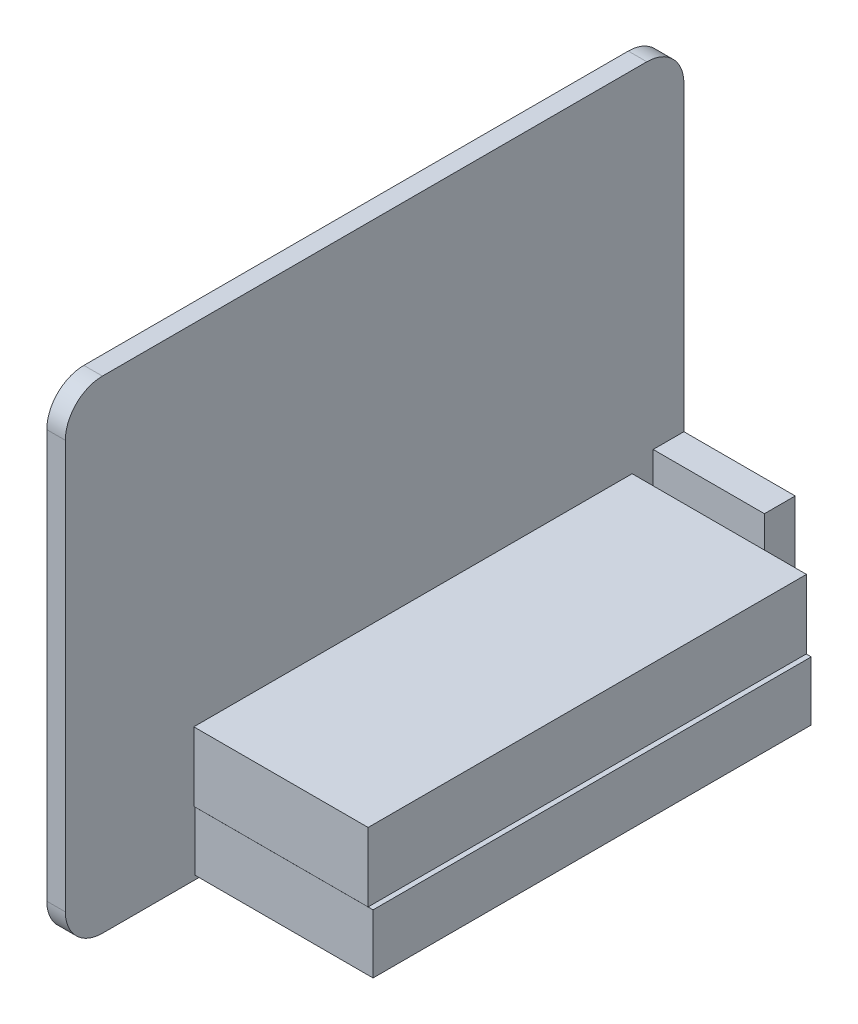
SolidWorks part; units mm, degrees
ref_plane "Front Plane" through (0, 0, 0) normal (0, 0, 1) x (1, 0, 0)
ref_plane "Top Plane" through (0, 0, 0) normal (0, 1, 0) x (1, 0, 0)
ref_plane "Right Plane" through (0, 0, 0) normal (1, 0, 0) x (0, 0, -1)
sketch "Sketch1" plane through (0, 0, 0) normal (1, 0, 0) x (0, 0, -1)
  line L1 (-15.4815, 15.6159) -> (131.2922, 15.6159)
  line L2 (-25.4815, 5.6159) -> (-25.4815, -104.4885)
  line L3 (-15.4815, -114.4885) -> (131.2922, -114.4885)
  line L4 (141.2922, 5.6159) -> (141.2922, -104.4885)
  arc A0 (131.2922, -114.4885) -> (141.2922, -104.4885) centre (131.2922, -104.4885) ccw
  arc A1 (-15.4815, -114.4885) -> (-25.4815, -104.4885) centre (-15.4815, -104.4885) cw
  arc A2 (-15.4815, 15.6159) -> (-25.4815, 5.6159) centre (-15.4815, 5.6159) ccw
  arc A3 (131.2922, 15.6159) -> (141.2922, 5.6159) centre (131.2922, 5.6159) cw
  dimension "D1" = 10
extrude "Boss-Extrude1" add sketch "Sketch1" along normal blind 5
sketch "Sketch2" plane through (5, 0, 0) normal (1, 0, 0) x (0, 0, -1)
  line L1 (127.3329, -78.5904) -> (9.1515, -78.5904)
  line L2 (127.3329, -78.5904) -> (127.3329, -97.1494)
  line L3 (127.3329, -97.1494) -> (9.1515, -97.1494)
  line L4 (9.1515, -78.5904) -> (9.1515, -97.1494)
extrude "Boss-Extrude4" add sketch "Sketch2" along normal blind 47
sketch "Sketch3" plane through (5, 0, 0) normal (1, 0, 0) x (0, 0, -1)
  line L1 (9.4854, -97.4922) -> (127.6118, -97.4922)
  line L2 (9.4854, -97.4922) -> (9.4854, -113.408)
  line L3 (9.4854, -113.408) -> (127.6118, -113.408)
  line L4 (127.6118, -97.4922) -> (127.6118, -113.408)
extrude "Boss-Extrude5" add sketch "Sketch3" along normal blind 48
sketch "Sketch4" plane through (5, 0, 0) normal (1, 0, 0) x (0, 0, -1)
  line L1 (132.9955, -102.0572) -> (141.2922, -102.0572)
  line L2 (132.9955, -102.0572) -> (132.9955, -75.7578)
  line L3 (132.9955, -75.7578) -> (141.2922, -75.7578)
  line L4 (141.2922, -102.0572) -> (141.2922, -75.7578)
extrude "Boss-Extrude6" add sketch "Sketch4" along normal blind 30
sketch "Sketch5" plane through (0, 0, -141.2922) normal (0, 0, -1) x (-1, 0, 0)
  line L0 (-25.4643, -97.9262) -> (-12.8104, -97.9262)
  line L2 (-31.1161, -91.5258) -> (-31.1161, -80.2755)
  line L3 (-31.1161, -80.2755) -> (-8.7312, -80.2755)
  line L4 (-8.7312, -90.2342) -> (-8.7312, -80.2755)
  line L5 (-12.8104, -97.9262) -> (-8.7312, -90.2342)
  line L6 (-31.1161, -91.5258) -> (-25.4643, -97.9262)
extrude "Cut-Extrude3" cut sketch "Sketch5" against normal blind 7
sketch "Sketch6" plane through (0, 0, -134.2922) normal (0, 0, -1) x (-1, 0, 0)
  line L1 (-26.1502, -88.5216) -> (-23.9328, -88.5216)
  line L2 (-26.1502, -88.5216) -> (-26.1502, -86.6815)
  line L3 (-26.1502, -86.6815) -> (-23.9328, -86.6815)
  line L4 (-23.9328, -88.5216) -> (-23.9328, -86.6815)
  line L5 (-14.7425, -88.5216) -> (-12.174, -88.5216)
  line L6 (-14.7425, -88.5216) -> (-14.7425, -86.6815)
  line L7 (-14.7425, -86.6815) -> (-12.174, -86.6815)
  line L8 (-12.174, -88.5216) -> (-12.174, -86.6815)
  line L9 (-20.8183, -93.7688) -> (-18.1948, -93.7688)
  line L10 (-20.8183, -93.7688) -> (-20.8183, -91.9667)
  line L11 (-20.8183, -91.9667) -> (-18.1948, -91.9667)
  line L12 (-18.1948, -93.7688) -> (-18.1948, -91.9667)
extrude "Boss-Extrude7" add sketch "Sketch6" along normal blind 7
